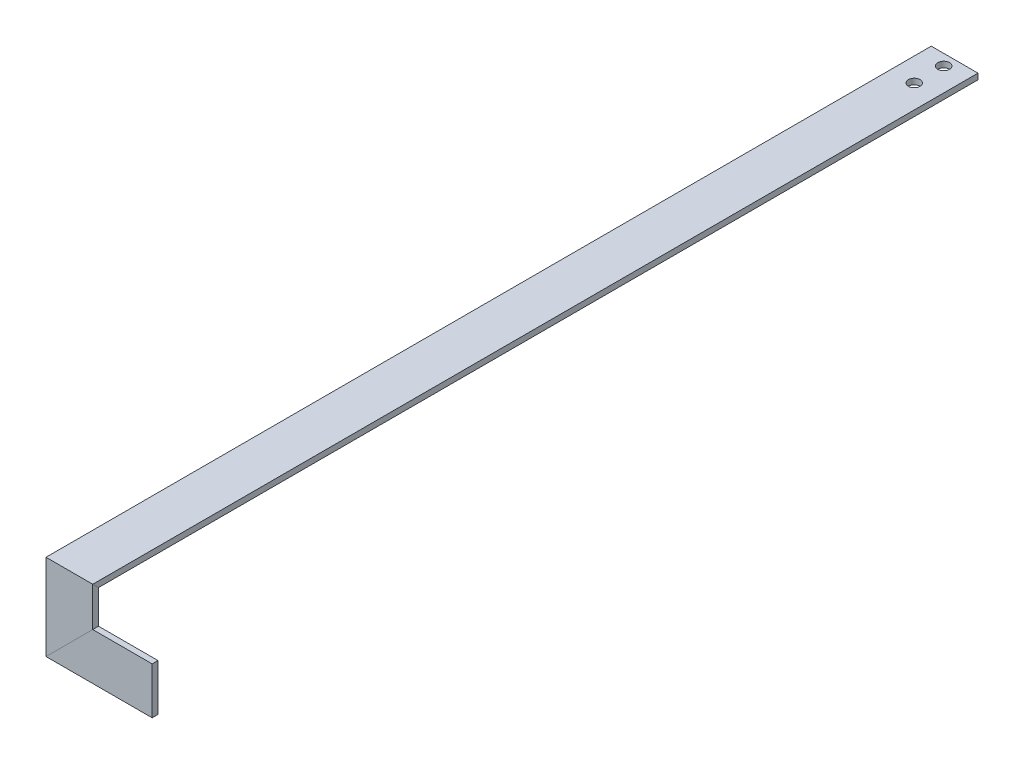
SolidWorks part; units mm, degrees
ref_plane "Alzado" through (0, 0, 0) normal (0, 0, 1) x (1, 0, 0)
ref_plane "Planta" through (0, 0, 0) normal (0, 1, 0) x (1, 0, 0)
ref_plane "Vista lateral" through (0, 0, 0) normal (1, 0, 0) x (0, 0, -1)
sketch "Croquis1" plane through (0, 0, 0) normal (0, 0, 1) x (1, 0, 0)
  line L1 (-25.4, 3.155) -> (25.4, 3.155)
  line L2 (-25.4, 3.155) -> (-25.4, -3.155)
  line L3 (-25.4, -3.155) -> (25.4, -3.155)
  line L4 (25.4, 3.155) -> (25.4, -3.155)
  line L5 (-25.4, 3.155) -> (25.4, -3.155) construction
  line L6 (-25.4, -3.155) -> (25.4, 3.155) construction
  point P0 (0, 0)
  dimension "D1" = 50.8
  dimension "D2" = 6.31
sketch3d "Croquis3D2"
  line L0 (0, 0, 0) -> (0, 0, 958.84)
  line L1 (0, 0, 958.84) -> (0, -64.9, 958.84)
  line L2 (0, -64.9, 958.84) -> (90, -64.9, 958.84)
  dimension "D1" = 958.84
  dimension "D2" = 64.9
  dimension "D3" = 90
sweep "Barrer1" add profiles "Croquis1" path "Croquis3D2"
sketch "Croquis2" plane through (0, 3.155, 0) normal (0, 1, 0) x (1, 0, 0)
  circle A0 centre (0, -43.8922) radius 6.35
  circle A1 centre (0, -11.8922) radius 6.35
extrude "Cortar-Extruir1" cut sketch "Croquis2" against normal blind 6.31
